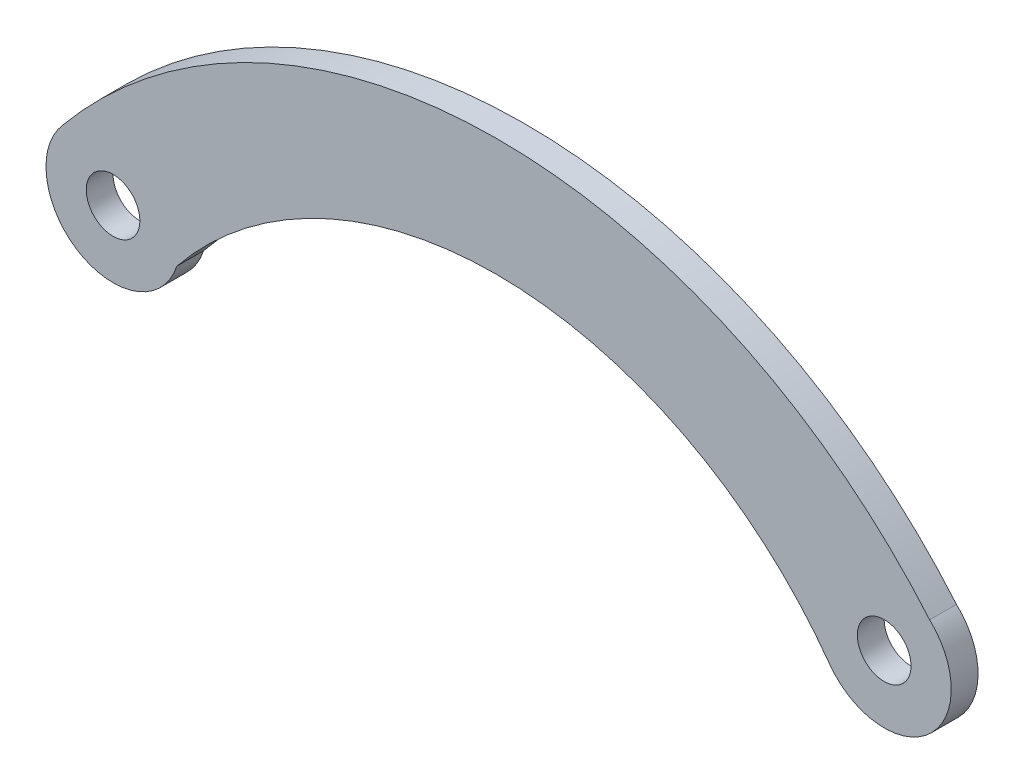
SolidWorks part; units mm, degrees
ref_plane "Front Plane" through (0, 0, 0) normal (0, 0, 1) x (1, 0, 0)
ref_plane "Top Plane" through (0, 0, 0) normal (0, 1, 0) x (1, 0, 0)
ref_plane "Right Plane" through (0, 0, 0) normal (1, 0, 0) x (0, 0, -1)
sketch "Sketch1" plane through (0, 0, 0) normal (0, 0, 1) x (1, 0, 0)
  arc A0 (53.4385, -2.9162) -> (4.7521, -1.5547) centre (28.5771, -20.7672) ccw
  circle A2 centre (0, 0) radius 2
  circle A3 centre (57.5, 0) radius 2
  arc A4 (60.8904, 3.6749) -> (-3.7427, 3.3154) centre (28.7238, -23.4714) ccw
  arc A6 (53.4385, -2.9162) -> (60.8904, 3.6749) centre (57.5, 0) ccw
  arc A7 (-3.7427, 3.3154) -> (4.7521, -1.5547) centre (0, 0) ccw
  dimension "D5" = 4
  dimension "D6" = 4
  dimension "D3" = 57.5
extrude "Boss-Extrude1" add sketch "Sketch1" along normal blind 2
